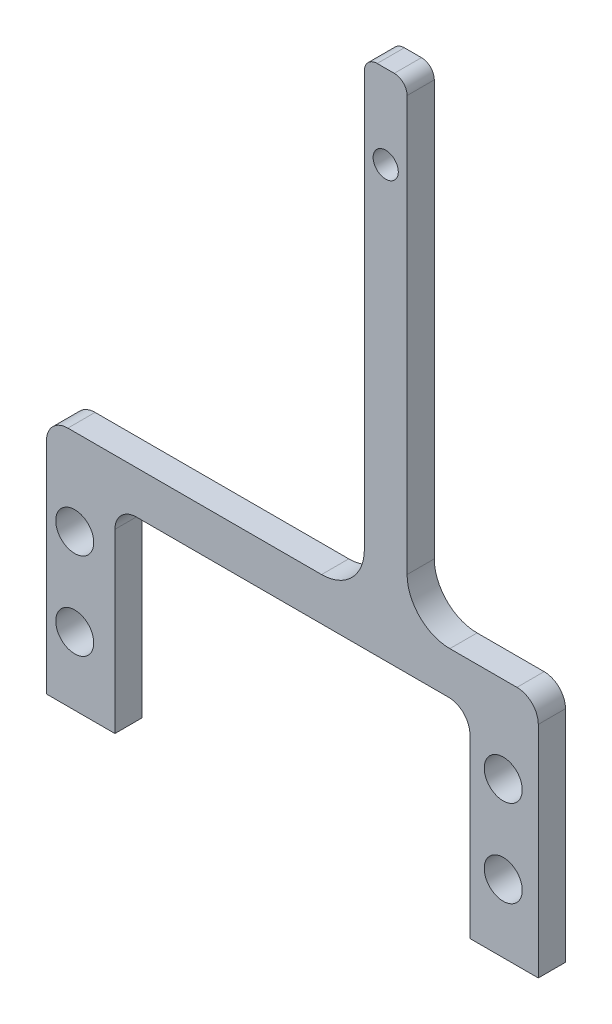
SolidWorks part; units mm, degrees
ref_plane "Front Plane" through (0, 0, 0) normal (0, 0, 1) x (1, 0, 0)
ref_plane "Top Plane" through (0, 0, 0) normal (0, 1, 0) x (1, 0, 0)
ref_plane "Right Plane" through (0, 0, 0) normal (1, 0, 0) x (0, 0, -1)
sketch "Sketch1" plane through (0, 0, 0) normal (0, 0, 1) x (1, 0, 0)
  line L0 (-20.75, 0) -> (20.75, 0) construction
  line L1 (28.75, 15) -> (13.41, 15)
  line L3 (-28.75, 15) -> (-28.75, -10)
  line L4 (-28.75, -10) -> (-20.75, -10)
  line L5 (-20.75, 10) -> (-20.75, -10)
  line L7 (20.75, 10) -> (20.75, -10)
  line L8 (20.75, -10) -> (28.75, -10)
  line L9 (28.75, 15) -> (28.75, -10)
  line L10 (20.75, 10) -> (-20.75, 10)
  line L11 (8.41, 15) -> (-28.75, 15)
  line L12 (13.41, 70) -> (8.41, 70)
  line L13 (13.41, 70) -> (13.41, 15)
  line L15 (8.41, 70) -> (8.41, 15)
  dimension "D1" = 41.5
  dimension "D2" = 20.75
  dimension "D3" = 8
  dimension "D4" = 8
  dimension "D5" = 25
  dimension "D6" = 37.16
  dimension "D7" = 5
  dimension "D8" = 5
  dimension "D9" = 55
extrude "Boss-Extrude1" add sketch "Sketch1" along normal blind 3.18
sketch "Sketch2" plane through (0, 0, 0) normal (0, 0, -1) x (-1, 0, 0)
  line L0 (-13.41, 70) -> (-8.41, 70) construction
  line L1 (-8.41, 70) -> (-10.91, 70) construction
  line L2 (-10.91, 70) -> (-10.91, 49.4951) construction
  circle A0 centre (-10.91, 60.25) radius 1.47
  dimension "D2" = 2.94
  dimension "D1" = 9.75
extrude "Cut-Extrude1" cut sketch "Sketch2" against normal through all
sketch "Sketch5" plane through (0, -10, 0) normal (0, -1, 0) x (1, 0, 0)
  line L1 (28.75, 0) -> (20.75, 0)
  line L2 (28.75, 0) -> (28.75, 3.18)
  line L3 (28.75, 3.18) -> (20.75, 3.18)
  line L4 (20.75, 0) -> (20.75, 3.18)
  line L5 (-20.75, 0) -> (-28.75, 0)
  line L6 (-20.75, 0) -> (-20.75, 3.18)
  line L7 (-20.75, 3.18) -> (-28.75, 3.18)
  line L8 (-28.75, 0) -> (-28.75, 3.18)
extrude "Boss-Extrude2" add sketch "Sketch5" along normal blind 3.18
sketch "Sketch6" plane through (0, 0, 3.18) normal (0, 0, 1) x (1, 0, 0)
  circle A0 centre (-25.449, 4.9225) radius 2.2225
  circle A1 centre (-25.449, -5.2375) radius 2.2225
  circle A2 centre (24.649, 4.9225) radius 2.2225
  circle A3 centre (24.649, -5.2375) radius 2.2225
extrude "Cut-Extrude2" cut sketch "Sketch6" against normal through all
fillet "Fillet1" radius 5 2 edges at (8.41, 15, 1.59) (13.41, 15, 1.59)
fillet "Fillet2" radius 1.5 2 edges at (8.41, 70, 1.59) (13.41, 70, 1.59)
fillet "Fillet3" radius 2.5 4 edges at (20.75, 10, 1.59) (-20.75, 10, 1.59) (-28.75, 15, 1.59) (28.75, 15, 1.59)
